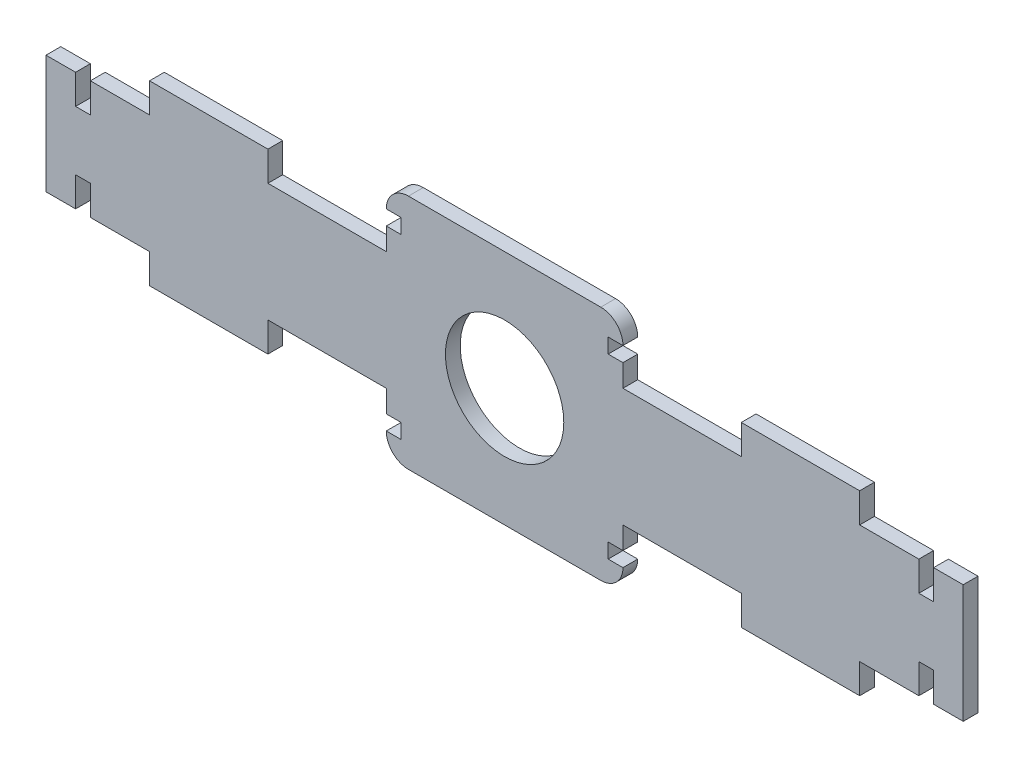
SolidWorks part; units mm, degrees
ref_plane "Front Plane" through (0, 0, 0) normal (0, 0, 1) x (1, 0, 0)
ref_plane "Top Plane" through (0, 0, 0) normal (0, 1, 0) x (1, 0, 0)
ref_plane "Right Plane" through (0, 0, 0) normal (1, 0, 0) x (0, 0, -1)
sketch "Sketch2" plane through (0, 0, 0) normal (0, 0, 1) x (1, 0, 0)
  line L0 (0, 25.4) -> (0, -25.4)
  line L1 (-98.425, 25.4) -> (98.425, 25.4)
  line L2 (-98.425, 25.4) -> (-98.425, -25.4)
  line L3 (-98.425, -25.4) -> (98.425, -25.4)
  line L4 (98.425, 25.4) -> (98.425, -25.4)
  line L5 (-98.425, 25.4) -> (98.425, -25.4) construction
  line L6 (-98.425, -25.4) -> (98.425, 25.4) construction
  circle A0 centre (0, 0) radius 12.7
  point P0 (0, 0)
  dimension "D3" = 25.4
  dimension "D1" = 196.85
  dimension "D2" = 50.8
extrude "Boss-Extrude1" add sketch "Sketch2" along normal blind 3.175 contours A0 L0 L1 L2 L3 | A0 L0 L3 L4 L1
sketch "Sketch6" plane through (0, 0, 0) normal (0, 0, 1) x (1, 0, 0)
  line L0 (-20.6375, 25.4) -> (20.6375, 25.4)
  line L6 (-20.6375, -25.4) -> (20.6375, -25.4)
  line L8 (25.4, 12.7) -> (50.8, 12.7)
  line L9 (50.8, 12.7) -> (50.8, 19.05)
  line L10 (50.8, 19.05) -> (76.2, 19.05)
  line L11 (76.2, 19.05) -> (76.2, 12.7)
  line L12 (76.2, 12.7) -> (88.9, 12.7)
  line L15 (76.2, -12.7) -> (88.9, -12.7)
  line L16 (76.2, -19.05) -> (76.2, -12.7)
  line L17 (50.8, -19.05) -> (76.2, -19.05)
  line L18 (50.8, -12.7) -> (50.8, -19.05)
  line L19 (25.4, -12.7) -> (50.8, -12.7)
  line L20 (-25.4, -12.7) -> (-50.8, -12.7)
  line L21 (-50.8, -12.7) -> (-50.8, -19.05)
  line L22 (-50.8, -19.05) -> (-76.2, -19.05)
  line L23 (-76.2, -19.05) -> (-76.2, -12.7)
  line L24 (-76.2, -12.7) -> (-88.9, -12.7)
  line L25 (-76.2, 12.7) -> (-88.9, 12.7)
  line L26 (-76.2, 19.05) -> (-76.2, 12.7)
  line L27 (-50.8, 12.7) -> (-50.8, 19.05)
  line L28 (-50.8, 19.05) -> (-76.2, 19.05)
  line L29 (-25.4, 12.7) -> (-50.8, 12.7)
  line L30 (25.4, -12.7) -> (25.4, -17.4625)
  line L31 (-25.4, -17.4625) -> (-25.4, -12.7)
  line L32 (-25.4, 12.7) -> (-25.4, 17.4625)
  line L33 (98.425, 12.7) -> (98.425, -12.7)
  line L34 (-98.425, 12.7) -> (-98.425, -12.7)
  line L35 (76.2, 12.7) -> (88.9, 12.7)
  line L36 (88.9, 12.7) -> (88.9, 6.35)
  line L37 (88.9, 6.35) -> (92.075, 6.35)
  line L38 (92.075, 6.35) -> (92.075, 12.7)
  line L39 (92.075, 12.7) -> (98.425, 12.7)
  line L40 (92.075, -6.35) -> (92.075, -12.7)
  line L41 (88.9, -6.35) -> (92.075, -6.35)
  line L42 (88.9, -12.7) -> (88.9, -6.35)
  line L43 (92.075, -12.7) -> (98.425, -12.7)
  line L44 (92.075, -12.7) -> (98.425, -12.7)
  line L45 (92.075, 12.7) -> (98.425, 12.7)
  line L46 (-92.075, 6.35) -> (-92.075, 12.7)
  line L47 (-88.9, 12.7) -> (-88.9, 6.35)
  line L48 (-88.9, 6.35) -> (-92.075, 6.35)
  line L49 (-88.9, -6.35) -> (-92.075, -6.35)
  line L50 (-88.9, -12.7) -> (-88.9, -6.35)
  line L51 (-92.075, -6.35) -> (-92.075, -12.7)
  line L52 (-92.075, -12.7) -> (-98.425, -12.7)
  line L53 (-92.075, 12.7) -> (-98.425, 12.7)
  line L54 (-98.425, -12.7) -> (-98.425, -25.4)
  line L55 (-98.425, -25.4) -> (-25.4, -25.4)
  line L56 (25.4, -25.4) -> (98.425, -25.4)
  line L57 (98.425, -25.4) -> (98.425, -12.7)
  line L58 (98.425, 12.7) -> (98.425, 25.4)
  line L59 (98.425, 25.4) -> (25.4, 25.4)
  line L60 (-25.4, 25.4) -> (-98.425, 25.4)
  line L61 (-98.425, 25.4) -> (-98.425, 12.7)
  line L62 (25.4, 12.7) -> (25.4, 17.4625)
  line L63 (25.4, 17.4625) -> (22.225, 17.4625)
  line L64 (22.225, 17.4625) -> (22.225, 20.6375)
  line L65 (22.225, 20.6375) -> (25.4, 20.6375)
  line L66 (25.4, 17.4625) -> (25.4, 12.7)
  line L67 (25.4, 20.6375) -> (22.225, 20.6375)
  line L68 (25.4, 25.4) -> (20.6375, 25.4)
  line L69 (-25.4, 17.4625) -> (-22.225, 17.4625)
  line L70 (-22.225, 17.4625) -> (-22.225, 20.6375)
  line L71 (-22.225, 20.6375) -> (-25.4, 20.6375)
  line L72 (-25.4, 25.4) -> (-20.6375, 25.4)
  line L73 (-22.225, -20.6375) -> (-25.4, -20.6375)
  line L74 (-22.225, -17.4625) -> (-22.225, -20.6375)
  line L75 (-25.4, -17.4625) -> (-22.225, -17.4625)
  line L76 (25.4, -17.4625) -> (22.225, -17.4625)
  line L77 (22.225, -17.4625) -> (22.225, -20.6375)
  line L78 (22.225, -20.6375) -> (25.4, -20.6375)
  line L79 (25.4, -25.4) -> (20.6375, -25.4)
  line L80 (-20.6375, -25.4) -> (-25.4, -25.4)
  arc A1 (25.4, 20.6375) -> (20.6375, 25.4) centre (20.6375, 20.6375) ccw
  arc A2 (-25.4, 20.6375) -> (-20.6375, 25.4) centre (-20.6375, 20.6375) cw
  arc A3 (25.4, -20.6375) -> (20.6375, -25.4) centre (20.6375, -20.6375) cw
  arc A4 (-25.4, -20.6375) -> (-20.6375, -25.4) centre (-20.6375, -20.6375) ccw
extrude "Cut-Extrude3" cut sketch "Sketch6" along normal blind 3.175 contours L71 A2 L72 L60 L61 L53 L46 L48 L47 L25 L26 L28 L27 L29 L32 L69 L70 | A1 L65 L64 L63 L62 L8 L9 L10 L11 L12 L36 L37 L38 L39 L58 L59 L68 | A4 L73 L74 L75 L31 L20 L21 L22 L23 L24 L50 L49 L51 L52 L54 L55 L80 | L78 A3 L79 L56 L57 L43 L40 L41 L42 L15 L16 L17 L18 L19 L30 L76 L77
